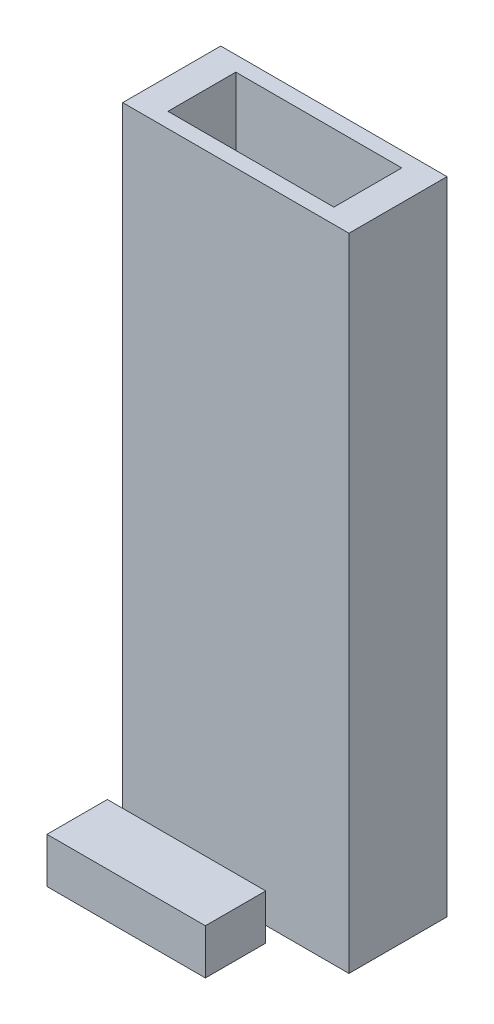
SolidWorks part; units mm, degrees
ref_plane "Front Plane" through (0, 0, 0) normal (0, 0, 1) x (1, 0, 0)
ref_plane "Top Plane" through (0, 0, 0) normal (0, 1, 0) x (1, 0, 0)
ref_plane "Right Plane" through (0, 0, 0) normal (1, 0, 0) x (0, 0, -1)
sketch "Sketch1" plane through (0, 0, 0) normal (0, 1, 0) x (1, 0, 0)
  line L1 (0, 0) -> (30, 0)
  line L2 (0, 0) -> (0, -13)
  line L3 (0, -13) -> (30, -13)
  line L4 (30, 0) -> (30, -13)
  dimension "D1" = 30
  dimension "D2" = 13
extrude "Boss-Extrude1" add sketch "Sketch1" along normal blind 85
sketch "Sketch2" plane through (0, 85, 0) normal (0, 1, 0) x (1, 0, 0)
  line L0 (0, -6.5) -> (30, -6.5) construction
  line L1 (0, 0) -> (0, -13) construction
  line L2 (30, -13) -> (30, 0) construction
  line L4 (4, -11) -> (26, -11)
  line L5 (4, -11) -> (4, -2)
  line L6 (4, -2) -> (26, -2)
  line L7 (26, -11) -> (26, -2)
  line L8 (4, -11) -> (26, -2) construction
  line L9 (4, -2) -> (26, -11) construction
  point P6 (15, -6.5)
  dimension "D1" = 22
  dimension "D2" = 9
extrude "Cut-Extrude2" cut sketch "Sketch2" against normal blind 85
sketch "Sketch4" plane through (0, 0, 0) normal (0, 1, 0) x (1, 0, 0)
  line L1 (0, -15.0364) -> (21, -15.0364)
  line L2 (0, -15.0364) -> (0, -23.0364)
  line L3 (0, -23.0364) -> (21, -23.0364)
  line L4 (21, -15.0364) -> (21, -23.0364)
  dimension "D1" = 21
  dimension "D2" = 8
extrude "Boss-Extrude2" add sketch "Sketch4" along normal blind 6 separate body
